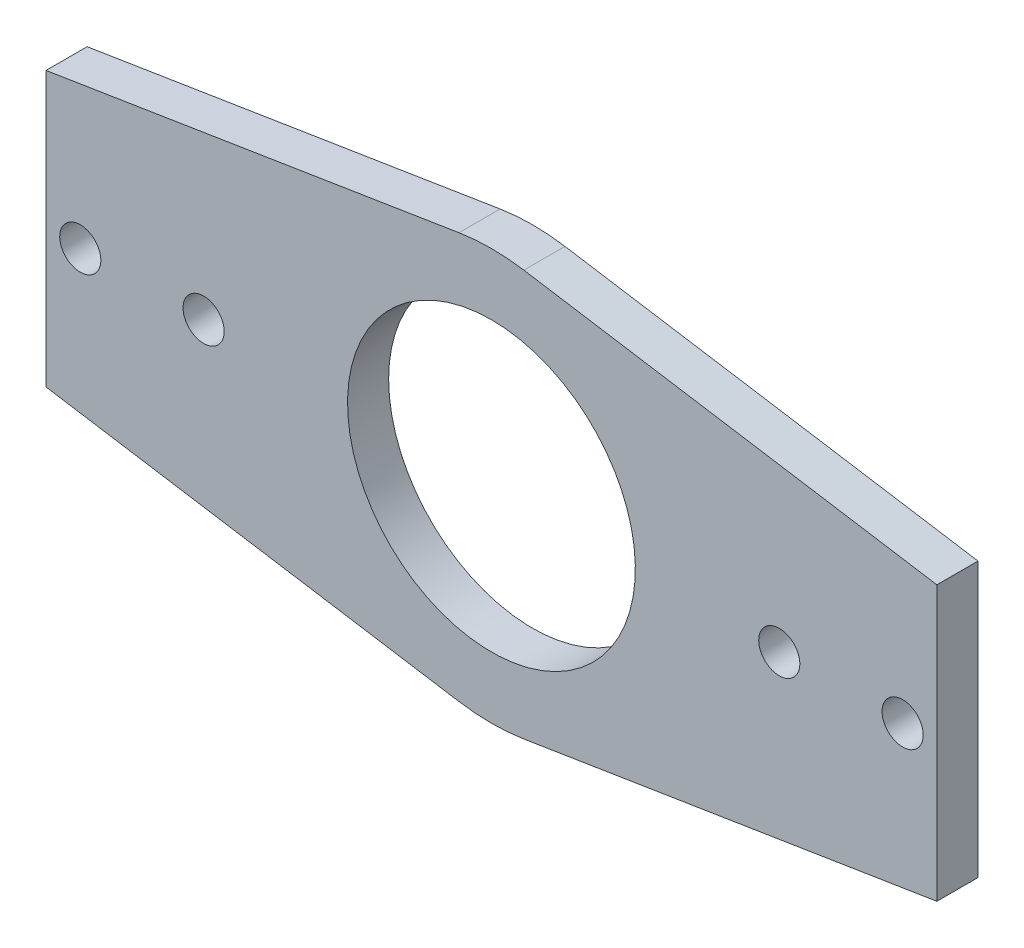
SolidWorks part; units mm, degrees
material "6063-O"
ref_plane "Front Plane" through (0, 0, 0) normal (0, 0, 1) x (1, 0, 0)
ref_plane "Top Plane" through (0, 0, 0) normal (0, 1, 0) x (1, 0, 0)
ref_plane "Right Plane" through (0, 0, 0) normal (1, 0, 0) x (0, 0, -1)
sketch "Sketch1" plane through (0, 0, 0) normal (0, 0, 1) x (1, 0, 0)
  line L0 (-65, 0) -> (65, 0) construction
  line L5 (-65, 20) -> (-65, -20)
  line L6 (-65, 20) -> (-4.7309, 29.6246)
  line L7 (-65, -20) -> (-4.7309, -29.6246)
  line L8 (0, 0) -> (0, 30) construction
  line L9 (65, -20) -> (4.7309, -29.6246)
  line L10 (65, 20) -> (65, -20)
  line L11 (65, 20) -> (4.7309, 29.6246)
  line L12 (-33, 25.1102) -> (-33, -25.1102) construction
  circle A0 centre (0, 0) radius 23.5 construction
  arc A1 (-4.7309, -29.6246) -> (4.7309, -29.6246) centre (0, 0) ccw
  circle A2 centre (60, 0) radius 3
  circle A3 centre (42, 0) radius 3
  arc A4 (4.7309, 29.6246) -> (-4.7309, 29.6246) centre (0, 0) ccw
  circle A5 centre (-60, 0) radius 3
  circle A6 centre (-42, 0) radius 3
  circle A7 centre (0, 0) radius 16
  circle A8 centre (60, 0) radius 4.4 construction
  point P7 (0, 0)
  point P10 (-65, 0)
  dimension "D1" = 47
  dimension "D2" = 60
  dimension "D5" = 6
  dimension "D7" = 6
  dimension "D9" = 32
  dimension "D3" = 130
  dimension "D4" = 40
  dimension "D10" = 33
  dimension "D11" = 84
extrude "Boss-Extrude1" add sketch "Sketch1" along normal blind 6
sketch "Sketch3" plane through (0, 0, 0) normal (0, 0, -1) x (-1, 0, 0)
  circle A0 centre (0, 0) radius 21
  circle A1 centre (0, 0) radius 30
  dimension "D1" = 42
  dimension "D2" = 60
extrude "Boss-Extrude3" add sketch "Sketch3" along normal blind 3.5
sketch "Sketch4" plane through (0, 0, 0) normal (0, 0, -1) x (-1, 0, 0)
  line L3 (4.7309, -29.6246) -> (65, -20)
  line L4 (65, -20) -> (65, 20)
  line L5 (65, 20) -> (4.7309, 29.6246)
  line L6 (4.7309, -29.6246) -> (65, -20)
  line L7 (65, -20) -> (65, 20)
  line L8 (65, 20) -> (4.7309, 29.6246)
  line L9 (-4.7309, 29.6246) -> (-65, 20)
  line L10 (-65, 20) -> (-65, -20)
  line L11 (-65, -20) -> (-4.7309, -29.6246)
  line L12 (-4.7309, 29.6246) -> (-65, 20)
  line L13 (-65, 20) -> (-65, -20)
  line L14 (-65, -20) -> (-4.7309, -29.6246)
  circle A0 centre (60, 0) radius 3 construction
  arc A1 (4.7309, -29.6246) -> (4.7309, 29.6246) centre (0, 0) ccw
  arc A2 (4.7309, -29.6246) -> (4.7309, 29.6246) centre (0, 0) ccw
  arc A3 (-4.7309, 29.6246) -> (-4.7309, -29.6246) centre (0, 0) ccw
  arc A4 (-4.7309, 29.6246) -> (-4.7309, -29.6246) centre (0, 0) ccw
  circle A5 centre (42, 0) radius 3 construction
  circle A6 centre (-42, 0) radius 3 construction
  circle A7 centre (-60, 0) radius 3 construction
  circle A8 centre (60, 0) radius 3
  circle A9 centre (42, 0) radius 3
  circle A10 centre (-42, 0) radius 3
  circle A11 centre (-60, 0) radius 3
  dimension "D1" = 0
  dimension "D2" = 0
extrude "Boss-Extrude4" add sketch "Sketch4" along normal blind 3.5
sketch "Sketch5" plane through (0, 0, -3.5) normal (0, 0, -1) x (-1, 0, 0)
  line L6 (-4.7309, 29.6246) -> (-65, 20)
  line L7 (-65, 20) -> (-65, -20)
  line L8 (-65, -20) -> (-4.7309, -29.6246)
  line L9 (4.7309, -29.6246) -> (65, -20)
  line L10 (65, -20) -> (65, 20)
  line L11 (65, 20) -> (4.7309, 29.6246)
  line L12 (-4.7309, 29.6246) -> (-65, 20)
  line L13 (-65, 20) -> (-65, -20)
  line L14 (-65, -20) -> (-4.7309, -29.6246)
  line L15 (4.7309, -29.6246) -> (65, -20)
  line L16 (65, -20) -> (65, 20)
  line L17 (65, 20) -> (4.7309, 29.6246)
  circle A0 centre (60, 0) radius 3 construction
  circle A1 centre (42, 0) radius 3 construction
  arc A2 (4.7309, 29.6246) -> (-4.7309, 29.6246) centre (0, 0) ccw
  arc A3 (-4.7309, -29.6246) -> (4.7309, -29.6246) centre (0, 0) ccw
  arc A4 (4.7309, 29.6246) -> (-4.7309, 29.6246) centre (0, 0) ccw
  arc A5 (-4.7309, -29.6246) -> (4.7309, -29.6246) centre (0, 0) ccw
  circle A6 centre (0, 0) radius 21 construction
  circle A7 centre (-42, 0) radius 3 construction
  circle A8 centre (-60, 0) radius 3 construction
  circle A9 centre (60, 0) radius 3
  circle A10 centre (42, 0) radius 3
  circle A11 centre (0, 0) radius 21
  circle A12 centre (-42, 0) radius 3
  circle A13 centre (-60, 0) radius 3
  dimension "D1" = 0
extrude "Cut-Extrude1" cut sketch "Sketch5" against normal blind 0.5
sketch "Sketch6" plane through (65, 0, 0) normal (1, 0, 0) x (0, 0, -1)
  line L0 (-3, 36.6838) -> (-3, -32.3162)
  line L8 (-6, 30) -> (-6, 29.6246) construction
  line L9 (-6, 29.8123) -> (-6, -32.3162)
  line L10 (-6, -32.3162) -> (-3, -32.3162)
  line L11 (-6, 29.8123) -> (-6, 36.6838)
  line L12 (-6, 36.6838) -> (-3, 36.6838)
  dimension "D1" = 3
extrude "Cut-Extrude2" cut sketch "Sketch6" against normal blind 182
sketch "Sketch7" plane through (0, 0, 0) normal (0, 0, -1) x (-1, 0, 0)
  circle A1 centre (0, 0) radius 21
  circle A2 centre (0, 0) radius 21
  dimension "D1" = 0
extrude "Cut-Extrude3" cut sketch "Sketch7" against normal blind 10
